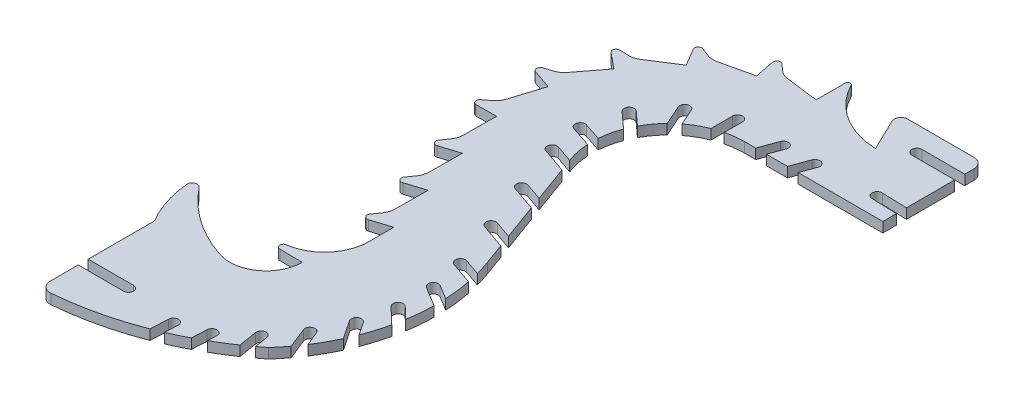
SolidWorks part; units mm, degrees
ref_plane "Front Plane" through (0, 0, 0) normal (0, 0, 1) x (1, 0, 0)
ref_plane "Top Plane" through (0, 0, 0) normal (0, 1, 0) x (1, 0, 0)
ref_plane "Right Plane" through (0, 0, 0) normal (1, 0, 0) x (0, 0, -1)
sketch "Sketch2" plane through (0, 0, 0) normal (0, 1, 0) x (1, 0, 0)
  line L0 (30.5917, -19.7066) -> (10.7709, -19.7066)
  line L1 (33.5917, -22.7066) -> (33.5917, -25.4348)
  line L2 (33.5917, -25.4348) -> (20.7417, -25.4348)
  line L3 (20.7417, -28.4348) -> (33.5917, -28.4348)
  line L4 (33.5917, -28.4348) -> (33.5917, -42.9048)
  line L5 (33.5917, -42.9048) -> (26.1131, -42.6436)
  line L6 (26.0084, -45.6418) -> (33.5917, -45.9066)
  line L7 (33.5917, -45.9066) -> (33.5917, -49.9666)
  line L8 (33.5917, -49.9666) -> (8.2315, -49.9666)
  line L9 (-13.2283, -50.6294) -> (-13.2283, -45.1294)
  line L10 (-38.0968, -90.3449) -> (-15.0449, -119.6181) construction
  line L11 (-16.2283, -45.1294) -> (-16.2283, -51.5914)
  line L12 (-21.75, -54.7438) -> (-23.977, -49.7148)
  line L13 (-26.7201, -50.9295) -> (-24.1036, -56.8382)
  line L14 (-27.876, -61.9563) -> (-31.9485, -58.2597)
  line L15 (-33.9648, -60.4811) -> (-29.18, -64.8243)
  line L16 (-30.557, -71.0316) -> (-35.7774, -69.3005)
  line L17 (-36.7216, -72.1481) -> (-30.588, -74.1819)
  line L18 (-1.2685, -49.9666) -> (0.3304, -45.6278)
  line L19 (-2.4846, -44.5905) -> (-4.4657, -49.9666)
  line L20 (8.2315, -49.9666) -> (9.8304, -45.6278)
  line L21 (7.0154, -44.5905) -> (5.0343, -49.9666)
  line L22 (5.0343, -49.9666) -> (-1.2685, -49.9666)
  line L23 (-4.4657, -49.9666) -> (-7.7629, -49.9666)
  line L24 (8.9698, -22.5761) -> (13.5917, -32.1501)
  line L25 (-7.9083, -19.7066) -> (-7.9083, -28.4348)
  line L26 (-7.9083, -28.4348) -> (-17.7173, -27.1905)
  line L27 (-24.1851, -25.227) -> (-23.0517, -31.1501)
  line L28 (-22.3684, -24.203) -> (-20.4348, -25.9451)
  line L29 (-38.0878, -32.1074) -> (-35.6757, -33.0849)
  line L30 (-39.4459, -33.6899) -> (-36.3591, -38.8705)
  line L31 (-23.0517, -31.1501) -> (-32.6963, -33.3282)
  line L32 (-50.1657, -44.9021) -> (-47.5649, -44.9977)
  line L33 (-50.9022, -46.8531) -> (-46.2327, -50.6691)
  line L34 (-36.3591, -38.8705) -> (-44.6814, -44.2095)
  line L35 (-57.1518, -61.0505) -> (-54.6745, -60.2528)
  line L36 (-57.1783, -63.1358) -> (-51.4867, -65.1291)
  line L37 (-46.2327, -50.6691) -> (-52.2331, -58.5278)
  line L38 (-58.2072, -78.6137) -> (-56.1509, -77.0184)
  line L39 (-57.5204, -80.5828) -> (-51.4903, -80.5139)
  line L40 (-51.4867, -65.1291) -> (-54.4448, -74.5637)
  line L41 (-35.2032, -82.0735) -> (-27.7919, -84.6414)
  line L42 (-34.2211, -79.2389) -> (-29.1162, -81.0076)
  line L43 (-29.3337, -80.4151) -> (-34.808, -80.9462) [skipped]
  line L44 (-34.5184, -83.9321) -> (-28.0865, -83.3082) [skipped]
  line L45 (-27.7919, -84.6414) -> (-23.8627, -95.4227)
  line L46 (-29.9498, -96.4886) -> (-22.5384, -99.0565)
  line L47 (-28.9676, -93.654) -> (-23.8627, -95.4227)
  line L48 (-24.6963, -110.9037) -> (-17.2849, -113.4716)
  line L49 (-23.7142, -108.0691) -> (-18.6093, -109.8378)
  line L50 (-19.4428, -125.3189) -> (-12.8043, -127.6189)
  line L51 (-18.4607, -122.4842) -> (-13.6103, -124.1647)
  line L52 (-17.6104, -135.4043) -> (-11.761, -138.9742)
  line L53 (-16.0476, -132.8435) -> (-11.8298, -135.4176)
  line L55 (-17.9659, -145.6487) -> (-13.1058, -150.2901)
  line L56 (-15.894, -143.4791) -> (-12.4305, -146.7867)
  line L57 (-13.2072, -136.8993) -> (-8.1023, -138.668) [skipped]
  line L58 (-14.1894, -139.734) -> (-6.778, -142.3018) [skipped]
  line L59 (-20.4932, -155.5829) -> (-16.78, -161.0812)
  line L60 (-18.0071, -153.9039) -> (-15.3857, -157.7855)
  line L61 (-25.0765, -164.7517) -> (-22.6311, -170.882)
  line L62 (-22.29, -163.6402) -> (-20.5743, -167.9412)
  line L63 (-31.5058, -172.7353) -> (-30.5908, -178.2262)
  line L64 (-28.5466, -172.2422) -> (-27.8723, -176.2883)
  line L65 (-39.4867, -179.1681) -> (-39.7092, -183.6785)
  line L66 (-36.4904, -179.3159) -> (-36.6228, -182.0006)
  line L67 (-47.9916, -182.1905) -> (-48.2552, -187.533)
  line L68 (-44.9953, -182.3383) -> (-45.1896, -186.2772)
  line L69 (-45.7574, -184.5372) -> (-47.0955, -189.4931) [skipped]
  line L70 (-48.6536, -183.7552) -> (-50.485, -190.538) [skipped]
  line L71 (-52.7779, -97.0537) -> (-47.0275, -95.2373)
  line L72 (-54.0068, -95.3688) -> (-52.5022, -93.2452)
  line L73 (-51.4903, -80.5139) -> (-51.5821, -90.401)
  line L74 (-48.3152, -111.7771) -> (-42.5647, -109.9607)
  line L75 (-49.544, -110.0922) -> (-48.0394, -107.9686)
  line L76 (-47.0275, -95.2373) -> (-47.1193, -105.1244)
  line L77 (-43.8524, -126.5004) -> (-38.102, -124.684)
  line L78 (-45.0813, -124.8156) -> (-43.5766, -122.692)
  line L79 (-42.5647, -109.9607) -> (-42.6566, -119.8478)
  line L80 (-38.102, -124.684) -> (-38.102, -132.0957)
  line L81 (-49.4878, -147.407) -> (-42.6952, -147.4701)
  line L82 (-75.5719, -158.8868) -> (-75.5719, -178.7068)
  line L83 (-22.5384, -99.0565) -> (-18.6093, -109.8378)
  line L84 (-17.2849, -113.4716) -> (-15.0449, -119.6181)
  line L85 (-75.5719, -181.7068) -> (-62.0122, -181.7068)
  line L86 (-62.0122, -178.7068) -> (-75.5719, -178.7068)
  line L87 (-75.5719, -181.7068) -> (-75.5719, -190.1036)
  arc A0 (-13.2283, -45.1294) -> (-16.2283, -45.1294) centre (-14.7283, -45.1294) ccw
  arc A1 (20.7417, -25.4348) -> (20.7417, -28.4348) centre (20.7417, -26.9348) ccw
  arc A2 (26.1131, -42.6436) -> (26.0084, -45.6418) centre (26.0608, -44.1427) ccw
  arc A3 (-7.7629, -49.9666) -> (-13.2283, -50.6294) centre (-7.7629, -72.8316) ccw
  arc A4 (-15.0449, -119.6181) -> (-13.6103, -124.1647) centre (-66.1611, -138.247) cw
  arc A5 (-25.7152, -174.6342) -> (-27.8723, -176.2883) centre (-79.6425, -106.5423) cw
  arc A6 (-23.977, -49.7148) -> (-26.7201, -50.9295) centre (-25.3485, -50.3222) ccw
  arc A7 (-31.9485, -58.2597) -> (-33.9648, -60.4811) centre (-32.9567, -59.3704) ccw
  arc A8 (-35.7774, -69.3005) -> (-36.7216, -72.1481) centre (-36.2495, -70.7243) ccw
  arc A9 (0.3304, -45.6278) -> (-2.4846, -44.5905) centre (-1.0771, -45.1092) ccw
  arc A10 (9.8304, -45.6278) -> (7.0154, -44.5905) centre (8.4229, -45.1092) ccw
  arc A11 (-20.4348, -25.9451) -> (-17.7173, -27.1905) centre (-17.0881, -22.2303) ccw
  arc A12 (-16.2283, -51.5914) -> (-21.75, -54.7438) centre (-7.7629, -72.8316) ccw
  arc A13 (-24.1036, -56.8382) -> (-27.876, -61.9563) centre (-7.7629, -72.8316) ccw
  arc A14 (-29.18, -64.8243) -> (-30.557, -71.0316) centre (-7.7629, -72.8316) ccw
  arc A15 (-30.588, -74.1819) -> (-29.1162, -81.0076) centre (-7.7629, -72.8316) ccw
  arc A16 (13.5917, -32.1501) -> (-6.4819, -19.3653) centre (14.3649, -8.7848) cw
  arc A17 (-6.4819, -19.3653) -> (-7.9083, -19.7066) centre (-7.1543, -19.7066) ccw
  arc A18 (-22.3684, -24.203) -> (-24.1851, -25.227) centre (-23.1047, -25.0203) ccw
  arc A19 (-35.6757, -33.0849) -> (-32.6963, -33.3282) centre (-33.7978, -28.451) ccw
  arc A20 (-38.0878, -32.1074) -> (-39.4459, -33.6899) centre (-38.501, -33.1269) ccw
  arc A21 (-47.5649, -44.9977) -> (-44.6814, -44.2095) centre (-47.3812, -40.001) ccw
  arc A22 (-50.1657, -44.9021) -> (-50.9022, -46.8531) centre (-50.2062, -46.0013) ccw
  arc A23 (-54.6745, -60.2528) -> (-52.2331, -58.5278) centre (-56.2071, -55.4935) ccw
  arc A24 (-57.1518, -61.0505) -> (-57.1783, -63.1358) centre (-56.8147, -62.0976) ccw
  arc A25 (-56.1509, -77.0184) -> (-54.4448, -74.5637) centre (-59.2158, -73.0679) ccw
  arc A26 (-58.2072, -78.6137) -> (-57.5204, -80.5828) centre (-57.5329, -79.4828) ccw
  arc A27 (-34.808, -80.9462) -> (-34.5184, -83.9321) centre (-34.6632, -82.4391) ccw [skipped]
  arc A28 (-35.2032, -82.0735) -> (-34.2211, -79.2389) centre (-34.7122, -80.6562) cw
  arc A29 (-29.9498, -96.4886) -> (-28.9676, -93.654) centre (-29.4587, -95.0713) cw
  arc A30 (-24.6963, -110.9037) -> (-23.7142, -108.0691) centre (-24.2052, -109.4864) cw
  arc A31 (-19.4428, -125.3189) -> (-18.4607, -122.4842) centre (-18.9518, -123.9015) cw
  arc A32 (-12.8043, -127.6189) -> (-11.8298, -135.4176) centre (-66.1611, -138.247) cw
  circle A33 centre (-7.7629, -72.8316) radius 44.3971 construction
  arc A34 (-17.6104, -135.4043) -> (-16.0476, -132.8435) centre (-16.829, -134.1239) cw
  arc A35 (-14.1894, -139.734) -> (-13.2072, -136.8993) centre (-13.6983, -138.3166) cw [skipped]
  arc A36 (-17.9659, -145.6487) -> (-15.894, -143.4791) centre (-16.93, -144.5639) cw
  arc A37 (-20.4932, -155.5829) -> (-18.0071, -153.9039) centre (-19.2502, -154.7434) cw
  arc A38 (-25.0765, -164.7517) -> (-22.29, -163.6402) centre (-23.6833, -164.196) cw
  arc A39 (-31.5058, -172.7353) -> (-28.5466, -172.2422) centre (-30.0262, -172.4888) cw
  arc A40 (-39.4867, -179.1681) -> (-36.4904, -179.3159) centre (-37.9885, -179.242) cw
  arc A41 (-47.9916, -182.1905) -> (-44.9953, -182.3383) centre (-46.4934, -182.2644) cw
  arc A42 (-48.6536, -183.7552) -> (-45.7574, -184.5372) centre (-47.2055, -184.1462) cw [skipped]
  arc A43 (-52.5022, -93.2452) -> (-51.5821, -90.401) centre (-56.5819, -90.3546) ccw
  arc A44 (-54.0068, -95.3688) -> (-52.7779, -97.0537) centre (-53.1093, -96.0048) ccw
  arc A45 (-49.544, -110.0922) -> (-48.3152, -111.7771) centre (-48.6465, -110.7282) ccw
  arc A46 (-48.0394, -107.9686) -> (-47.1193, -105.1244) centre (-52.1191, -105.078) ccw
  arc A47 (-45.0813, -124.8156) -> (-43.8524, -126.5004) centre (-44.1837, -125.4515) ccw
  arc A48 (-43.5766, -122.692) -> (-42.6566, -119.8478) centre (-47.6563, -119.8014) ccw
  arc A49 (-38.102, -132.0957) -> (-49.6306, -145.3105) centre (-51.44, -132.0957) cw
  arc A50 (-49.6306, -145.3105) -> (-49.4878, -147.407) centre (-49.4878, -146.3539) ccw
  arc A51 (-42.6952, -147.4701) -> (-57.0275, -157.7653) centre (-53.632, -147.3685) cw
  arc A52 (-57.0275, -157.7653) -> (-77.6013, -143.4683) centre (-43.5012, -116.3488) cw
  arc A53 (-77.6013, -143.4683) -> (-80.2278, -144.5253) centre (-78.7573, -144.3877) ccw
  arc A54 (-80.2278, -144.5253) -> (-75.5719, -158.8868) centre (-45.8128, -141.3035) ccw
  arc A55 (-22.6311, -170.882) -> (-25.7152, -174.6342) centre (-66.1611, -138.247) cw
  arc A56 (-30.5908, -178.2262) -> (-36.6228, -182.0006) centre (-79.6425, -106.5423) cw
  arc A57 (-39.7092, -183.6785) -> (-45.1896, -186.2772) centre (-79.6425, -106.5423) cw
  arc A58 (-48.2552, -187.533) -> (-82.1004, -193.3675) centre (-79.6425, -106.5423) cw construction
  arc A59 (-16.78, -161.0812) -> (-20.5743, -167.9412) centre (-66.1611, -138.247) cw
  arc A60 (-13.1058, -150.2901) -> (-15.3857, -157.7855) centre (-66.1611, -138.247) cw
  arc A61 (-11.761, -138.9742) -> (-12.4305, -146.7867) centre (-66.1611, -138.247) cw
  arc A62 (-62.0122, -181.7068) -> (-62.0122, -178.7068) centre (-62.0122, -180.2068) ccw
  arc A63 (10.7709, -19.7066) -> (8.9698, -22.5761) centre (10.7709, -21.7066) ccw
  arc A64 (30.5917, -19.7066) -> (33.5917, -22.7066) centre (30.5917, -22.7066) cw
  arc A65 (-48.2552, -187.533) -> (-72.3189, -193.093) centre (-79.6425, -106.5423) cw
  arc A66 (-72.3189, -193.093) -> (-75.5719, -190.1036) centre (-72.5719, -190.1036) cw
  point P30 (22.2417, -26.9348)
  point P31 (24.5617, -44.0904)
  point P36 (-14.7283, -43.6294)
  point P208 (-79.3087, -143.0175)
  point P222 (33.5917, -19.7066)
  point P223 (-75.5719, -193.3068)
  dimension "D1" = 22.865
  dimension "D4" = 54.405
  dimension "D6" = 40
  dimension "D7" = 86.86
  dimension "D12" = 1.5
  dimension "D10" = 56.11
  dimension "D22" = 41.5
  dimension "D23" = 187.229
  dimension "D25" = 1.1
  dimension "D27" = 5
  dimension "D33" = 6.1298
  dimension "D40" = 1.5
  dimension "D41" = 1.5
  dimension "D39" = 6.778
  dimension "D42" = 7.1543
  dimension "D43" = 8.1023
  dimension "D44" = 11.761
  dimension "D45" = 12.8043
  dimension "D46" = 13.2072
  dimension "D47" = 13.6103
  dimension "D48" = 15.3857
  dimension "D49" = 15.894
  dimension "D50" = 21.75
  dimension "D51" = 27.8723
  dimension "D74" = 2
  dimension "D75" = 3
  dimension "D76" = 3
  dimension "D2" = 120
  dimension "D3" = 37.26
  dimension "D5" = 62
  dimension "D8" = 46.82
  dimension "D9" = 4.06
  dimension "D11" = 9.03
  dimension "D13" = 2
  dimension "D14" = 11.35
  dimension "D15" = 30.26
  dimension "D16" = 14.47
  dimension "D17" = 7
  dimension "D21" = 20
  dimension "D24" = 10.833
  dimension "D26" = 1
  dimension "D31" = 50.35
  dimension "D32" = 4.8575
  dimension "D34" = 11.0799
  dimension "D35" = 2
  dimension "D37" = 34.42
  dimension "D38" = 11.6
  dimension "D52" = 42.6952
  dimension "D53" = 43.5012
  dimension "D54" = 44.9953
  dimension "D55" = 45.1896
  dimension "D56" = 45.8128
  dimension "D57" = 46.4934
  dimension "D58" = 49.4878
  dimension "D59" = 49.6306
  dimension "D60" = 51.44
  dimension "D61" = 53.632
  dimension "D62" = 57.0275
  dimension "D63" = 13.5596
  dimension "D65" = 79.3087
  dimension "D66" = 8.7848
  dimension "D67" = 33.0668
  dimension "D68" = 72.8316
  dimension "D69" = 5.6615
  dimension "D70" = 27.1379
  dimension "D71" = 9.5
  dimension "D72" = 5.9141
  dimension "D73" = 64.231
  dimension "D20" = 2
  dimension "D29" = 5
  dimension "D36" = 3
  dimension "D19" = 2
  dimension "D28" = 5
  dimension "D18" = 5
  dimension "D30" = 8
extrude "Boss-Extrude1" add sketch "Sketch2" along normal mid plane 3 contours A62 L85 L87 A58 L67 A41 L68 A57 L65 A40 L66 A56 L63 A39 L64 A5 A55 L61 A38 L62 A59 L59 A37 L60 A60 L55 A36 L56 A61 L52 A34 L53 A32 L50 A31 L51 A4 L84 L48 A30 L49 L83 L46 A29 L47 L45 L41 A28 L42 A15 L17
